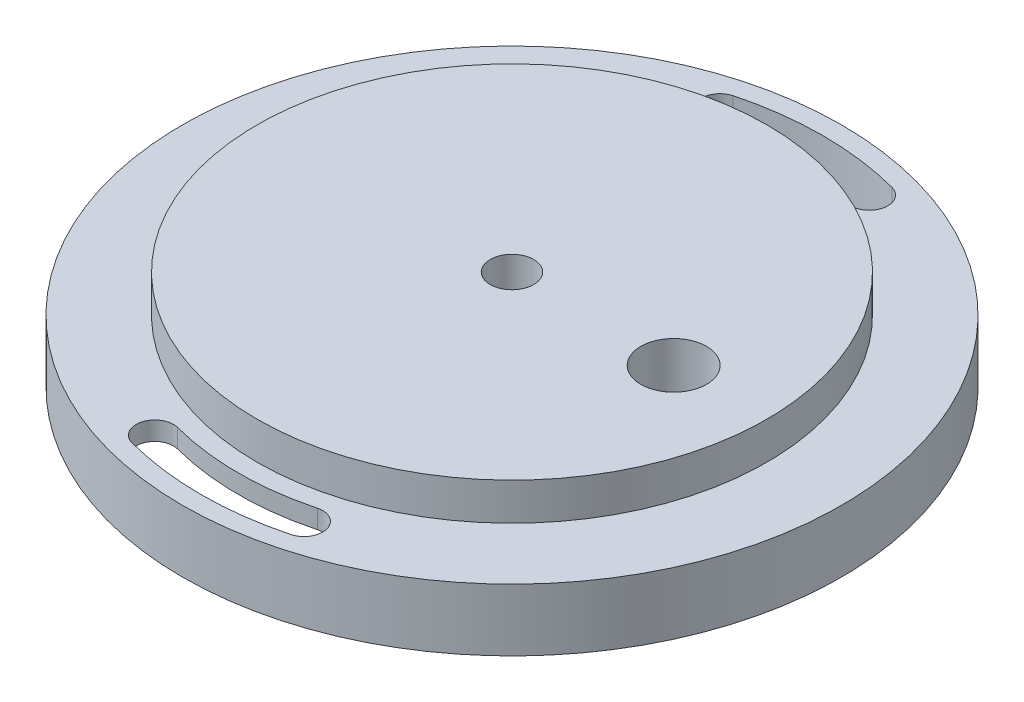
SolidWorks part; units mm, degrees
ref_plane "Спереди" through (0, 0, 0) normal (0, 0, 1) x (1, 0, 0)
ref_plane "Сверху" through (0, 0, 0) normal (0, 1, 0) x (1, 0, 0)
ref_plane "Справа" through (0, 0, 0) normal (1, 0, 0) x (0, 0, -1)
sketch "Эскиз1" plane through (0, 0, 0) normal (0, 0, 1) x (1, 0, 0)
  line L0 (0, 29.9005) -> (0, 56.6984) construction
  line L1 (-9, 29.9005) -> (8.9443, 29.9005) construction
  line L2 (-26.5, 30.6) -> (-26.5, 35.6)
  line L3 (-26.5, 35.6) -> (-20.5, 35.6)
  line L4 (-20.5, 35.6) -> (-20.5, 38.6)
  line L5 (-20.5, 38.6) -> (-1.75, 38.6)
  line L8 (-1.75, 34.1) -> (-24.5239, 34.1)
  line L9 (-24.5239, 34.1) -> (-25, 34.1)
  line L10 (-25, 34.1) -> (-25, 30.6)
  line L11 (-25, 30.6) -> (-26.5, 30.6)
  line L13 (-1.75, 38.6) -> (-1.75, 34.1)
  dimension "D1" = 3
  dimension "D2" = 5
  dimension "D3" = 41
  dimension "D4" = 1.5
  dimension "D5" = 6
  dimension "D6" = 1.5
  dimension "D7" = 3.5
revolve "Повернуть1" add sketch "Эскиз1" angle 360 about L0
sketch "Эскиз3" plane through (0, 0, 0) normal (0, 0, 1) x (1, 0, 0)
  line L0 (0, 30.6) -> (0, 38.6) construction
  line L1 (-26.5, 30.6) -> (26.5, 30.6) construction
  line L2 (20.5, 38.6) -> (-20.5, 38.6) construction
  line L3 (13, 30.6) -> (13, 38.6) construction
  line L4 (13, 38.6) -> (10.3544, 38.6)
  line L5 (10.3544, 38.6) -> (10.3544, 33.1074)
  line L6 (10.3544, 33.1074) -> (13, 33.1074)
  line L7 (13, 33.1074) -> (13, 38.6)
  dimension "D1" = 13
revolve "Вырез-Повернуть1" cut sketch "Эскиз3" angle 360 about L3
sketch "Эскиз4" plane through (0, 35.6, 0) normal (0, 1, 0) x (1, 0, 0)
  line L0 (0, 0) -> (0, -34.3012) construction
  line L1 (-6, -22.7211) -> (6, -22.7211) construction
  line L2 (0, 0) -> (-8.7543, 0) construction
  arc A0 (-5.617, -21.2709) -> (5.617, -21.2709) centre (0, 0) ccw
  arc A2 (-6.383, -24.1714) -> (6.383, -24.1714) centre (0, 0) ccw
  circle A3 centre (0, 0) radius 23.5 construction
  circle A7 centre (0, 0) radius 22 construction
  arc A8 (-5.617, -21.2709) -> (-6.383, -24.1714) centre (-6, -22.7211) ccw
  circle A9 centre (0, 0) radius 25 construction
  arc A10 (6.383, -24.1714) -> (5.617, -21.2709) centre (6, -22.7211) ccw
  arc A11 (6.383, 24.1714) -> (5.617, 21.2709) centre (6, 22.7211) cw
  arc A12 (-6.383, 24.1714) -> (6.383, 24.1714) centre (0, 0) cw
  arc A13 (-5.617, 21.2709) -> (-6.383, 24.1714) centre (-6, 22.7211) cw
  arc A14 (-5.617, 21.2709) -> (5.617, 21.2709) centre (0, 0) cw
  point P3 (-0.1891, 0)
  point P4 (23.6392, 7.3304)
  point P6 (25.5, 0)
  point P11 (22.5, 0)
  point P16 (20.7702, 6.4533)
  dimension "D4" = 12
  dimension "D1" = 47
  dimension "D2" = 1.5
  dimension "D5" = 50
  dimension "D6" = 44
  dimension "D3" = 1.5
sketch "Эскиз5" plane through (0, 35.6, 0) normal (0, 1, 0) x (1, 0, 0)
  line L0 (0, 0) -> (-9.8721, 0) construction
  line L1 (0, 0) -> (0, -33.417) construction
  line L2 (-6, -22.7211) -> (6, -22.7211) construction
  circle A0 centre (0, 0) radius 23.5 construction
  arc A1 (-5.617, -21.2709) -> (-6.383, -24.1714) centre (-6, -22.7211) ccw
  arc A2 (6.383, -24.1714) -> (5.617, -21.2709) centre (6, -22.7211) ccw
  circle A4 centre (0, -23.5) radius 1.5 construction
  arc A5 (-5.617, -21.2709) -> (5.617, -21.2709) centre (0, 0) ccw
  arc A6 (-6.383, -24.1714) -> (6.383, -24.1714) centre (0, 0) ccw
  arc A7 (6.383, 24.1714) -> (5.617, 21.2709) centre (6, 22.7211) cw
  arc A8 (-6.383, 24.1714) -> (6.383, 24.1714) centre (0, 0) cw
  arc A9 (-5.617, 21.2709) -> (-6.383, 24.1714) centre (-6, 22.7211) cw
  arc A10 (-5.617, 21.2709) -> (5.617, 21.2709) centre (0, 0) cw
  dimension "D2" = 3
  dimension "D3" = 3
  dimension "D1" = 12
extrude "Вырез-Вытянуть2" cut sketch "Эскиз5" against normal blind 20
extrude "Вырез-Вытянуть1" cut sketch "Эскиз4" against normal blind 10
